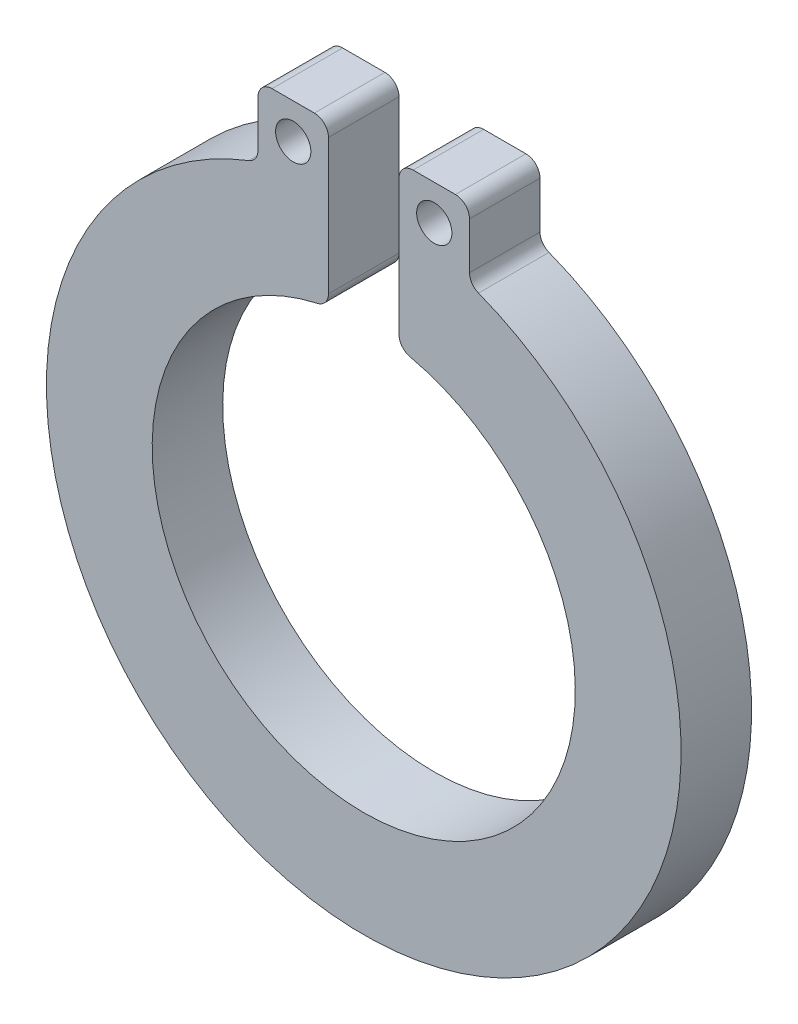
SolidWorks part; units mm, degrees
material "AISI 304"
ref_plane "Front Plane" through (0, 0, 0) normal (0, 0, 1) x (1, 0, 0)
ref_plane "Top Plane" through (0, 0, 0) normal (0, 1, 0) x (1, 0, 0)
ref_plane "Right Plane" through (0, 0, 0) normal (1, 0, 0) x (0, 0, -1)
sketch "Sketch1" plane through (0, 0, 0) normal (0, 0, 1) x (1, 0, 0)
  line L0 (-0.25, 2.6213) -> (-0.25, 1.479)
  line L1 (0.25, 2.6213) -> (0.25, 1.479)
  line L3 (-0.25, 2.6213) -> (-0.75, 2.6213)
  line L4 (-0.75, 2.6213) -> (-0.75, 2.1213)
  line L5 (0, -2.6792) -> (0, 2.6792) construction
  line L7 (0.75, 2.6213) -> (0.75, 2.1213)
  line L8 (0.25, 2.6213) -> (0.75, 2.6213)
  arc A0 (-0.25, 1.479) -> (0.25, 1.479) centre (0, 0) ccw
  arc A1 (-0.75, 2.1213) -> (0.75, 2.1213) centre (0, 0) ccw
  circle A2 centre (-0.5, 2.3713) radius 0.125
  circle A3 centre (0.5, 2.3713) radius 0.125
  point P14 (0.5, 2.3713)
  point P15 (-0.5, 2.3713)
  dimension "D1" = 3
  dimension "D2" = 4.5
  dimension "D10" = 0.25
  dimension "D3" = 0.5
  dimension "D4" = 0.5
  dimension "D5" = 0.5
  dimension "D6" = 0.25
  dimension "D7" = 0.25
  dimension "D8" = 0.25
  dimension "D9" = 0.25
extrude "Boss-Extrude1" add sketch "Sketch1" along normal blind 0.5
fillet "Fillet1" radius 0.1 8 edges at (-0.75, 2.6213, 0.25) (-0.25, 2.6213, 0.25) (0.25, 2.6213, 0.25) (0.75, 2.6213, 0.25) (0.75, 2.1213, 0.25) (-0.75, 2.1213, 0.25) (0.25, 1.479, 0.25) (-0.25, 1.479, 0.25)
